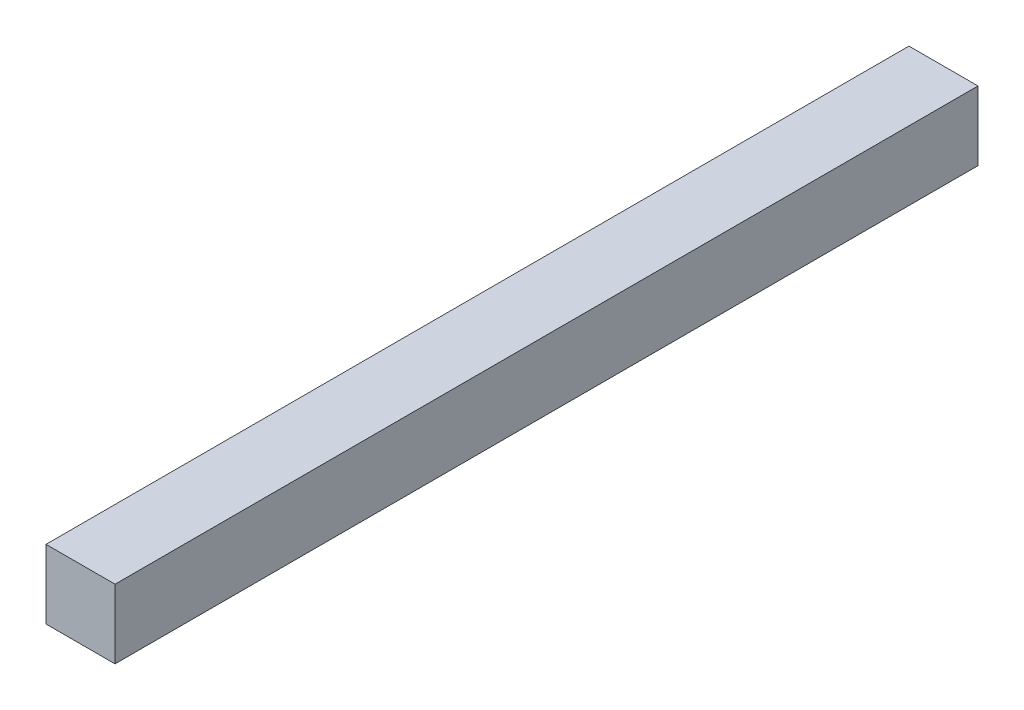
SolidWorks part; units mm, degrees
ref_plane "正面" through (0, 0, 0) normal (0, 0, 1) x (1, 0, 0)
ref_plane "平面" through (0, 0, 0) normal (0, 1, 0) x (1, 0, 0)
ref_plane "右側面" through (0, 0, 0) normal (1, 0, 0) x (0, 0, -1)
sketch "ｽｹｯﾁ1" plane through (0, 0, 0) normal (0, 0, 1) x (1, 0, 0)
  line L1 (0, 0) -> (80, 0)
  line L2 (0, 0) -> (0, 80)
  line L3 (0, 80) -> (80, 80)
  line L4 (80, 0) -> (80, 80)
  dimension "D1" = 80
  dimension "D2" = 80
extrude "ﾎﾞｽ - 押し出し1" add sketch "ｽｹｯﾁ1" along normal blind 1000
